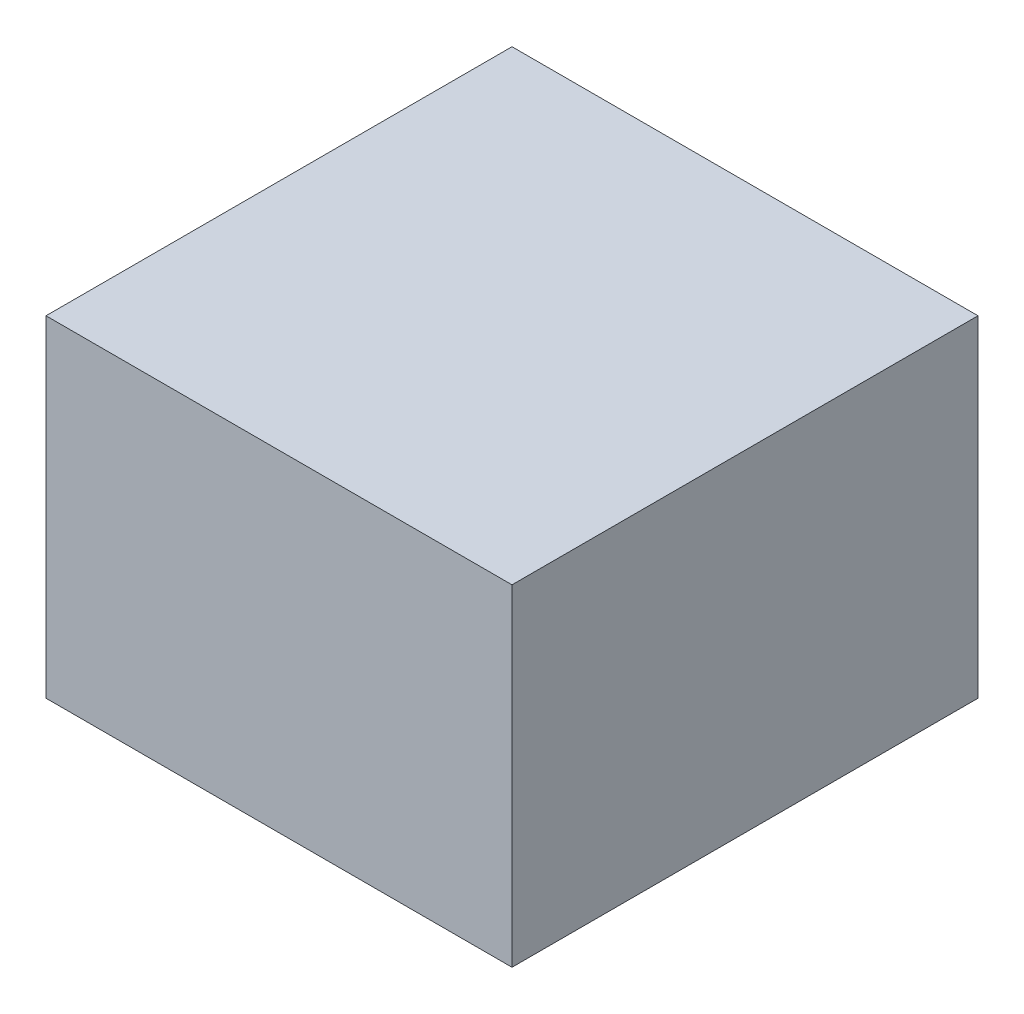
SolidWorks part; units mm, degrees
ref_plane "前视基准面" through (0, 0, 0) normal (0, 0, 1) x (1, 0, 0)
ref_plane "上视基准面" through (0, 0, 0) normal (0, 1, 0) x (1, 0, 0)
ref_plane "右视基准面" through (0, 0, 0) normal (1, 0, 0) x (0, 0, -1)
other "Configuration Table"
sketch "草图1" plane through (0, 0, 0) normal (0, 1, 0) x (1, 0, 0)
  line L1 (-18.5, -18.5) -> (18.5, -18.5)
  line L2 (-18.5, -18.5) -> (-18.5, 18.5)
  line L3 (-18.5, 18.5) -> (18.5, 18.5)
  line L4 (18.5, -18.5) -> (18.5, 18.5)
  line L5 (-18.5, -18.5) -> (18.5, 18.5) construction
  line L6 (-18.5, 18.5) -> (18.5, -18.5) construction
  point P0 (0, 0)
  dimension "D1" = 37
  dimension "D2" = 37
extrude "凸台-拉伸1" add sketch "草图1" along normal blind 26.3
sketch "草图2" plane through (0, 0, 0) normal (0, -1, 0) x (1, 0, 0)
  line L1 (-14.25, -14.25) -> (14.25, -14.25) construction
  line L2 (-14.25, -14.25) -> (-14.25, 14.25) construction
  line L3 (-14.25, 14.25) -> (14.25, 14.25) construction
  line L4 (14.25, -14.25) -> (14.25, 14.25) construction
  line L5 (-14.25, -14.25) -> (14.25, 14.25) construction
  line L6 (-14.25, 14.25) -> (14.25, -14.25) construction
  circle A0 centre (-14.25, 14.25) radius 1
  circle A1 centre (14.25, 14.25) radius 1
  circle A2 centre (14.25, -14.25) radius 1
  circle A3 centre (-14.25, -14.25) radius 1
  point P0 (0, 0)
  point P16 (0, 0)
  dimension "D3" = 2
  dimension "D1" = 28.5
  dimension "D2" = 28.5
  dimension "D4" = 4
extrude "切除-拉伸1" cut sketch "草图2" against normal blind 8
